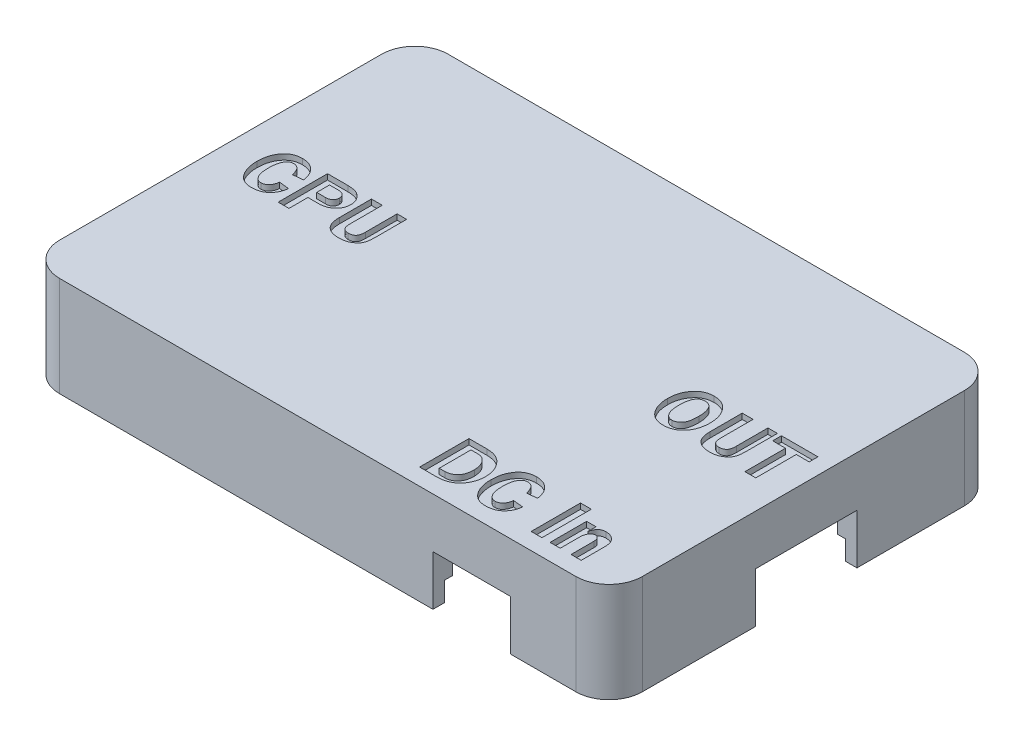
SolidWorks part; units mm, degrees
ref_plane "Front Plane" through (0, 0, 0) normal (0, 0, 1) x (1, 0, 0)
ref_plane "Top Plane" through (0, 0, 0) normal (0, 1, 0) x (1, 0, 0)
ref_plane "Right Plane" through (0, 0, 0) normal (1, 0, 0) x (0, 0, -1)
sketch "Sketch1" plane through (0, 0, 0) normal (0, 1, 0) x (1, 0, 0)
  line L1 (-52.5, 35) -> (52.5, 35)
  line L2 (-52.5, 35) -> (-52.5, -35)
  line L3 (-52.5, -35) -> (52.5, -35)
  line L4 (52.5, 35) -> (52.5, -35)
  line L5 (-52.5, 35) -> (52.5, -35) construction
  line L6 (-52.5, -35) -> (52.5, 35) construction
  point P0 (0, 0)
  dimension "D1" = 105
  dimension "D2" = 70
extrude "Boss-Extrude1" add sketch "Sketch1" along normal blind 15
sketch "Sketch3" plane through (0, 15, 0) normal (0, 1, 0) x (1, 0, 0)
  line L0 (52.5, -35) -> (52.5, 35) construction
  line L1 (49, -31.5) -> (-49, -31.5)
  line L2 (49, -31.5) -> (49, 31.5)
  line L3 (49, 31.5) -> (-49, 31.5)
  line L4 (-49, -31.5) -> (-49, 31.5)
  line L5 (49, -31.5) -> (-49, 31.5) construction
  line L6 (49, 31.5) -> (-49, -31.5) construction
  line L7 (-52.5, -35) -> (52.5, -35) construction
  point P0 (0, 0)
  dimension "D1" = 3.5
  dimension "D2" = 3.5
extrude "Cut-Extrude1" cut sketch "Sketch3" against normal blind 12
fillet "Fillet1" radius 6 8 edges at (-52.5, 7.5, -35) (-52.5, 7.5, 35) (52.5, 7.5, -35) (52.5, 7.5, 35) (49, 9, -31.5) (-49, 9, -31.5) (-49, 9, 31.5) (49, 9, 31.5)
sketch "Sketch4" plane through (0, 3, 0) normal (0, 1, 0) x (1, 0, 0)
  line L0 (-43, -31.5) -> (43, -31.5) construction
  line L1 (49, -25.5) -> (49, 25.5) construction
  circle A0 centre (40, -22.5) radius 3.5
  circle A1 centre (40, 19.2) radius 3.5
  circle A2 centre (-36.1, -22.5) radius 3.5
  circle A3 centre (-36.1, 19.2) radius 3.5
  dimension "D5" = 7
  dimension "D6" = 76.1
  dimension "D1" = 41.7
  dimension "D2" = 9
  dimension "D3" = 76.1
  dimension "D4" = 9
  dimension "D7" = 41.7
extrude "Boss-Extrude2" [suppressed] add sketch "Sketch4" along normal blind 5
sketch "Sketch5" [suppressed] plane through (0, 8, 0) normal (0, 1, 0) x (1, 0, 0)
  circle A0 centre (-36.1, 19.2) radius 1
  circle A1 centre (-36.1, -22.5) radius 1
  circle A2 centre (40, -22.5) radius 1
  circle A3 centre (40, 19.0603) radius 1
  dimension "D1" = 2
extrude "Cut-Extrude2" [suppressed] cut sketch "Sketch5" against normal blind 8
sketch "Sketch6" plane through (0, 15, 0) normal (0, 1, 0) x (1, 0, 0)
  line L0 (49, -25.5) -> (49, 25.5) construction
  line L1 (49, 9.66) -> (52.5, 9.66)
  line L2 (49, 9.66) -> (49, -8.64)
  line L3 (49, -8.64) -> (52.5, -8.64)
  line L4 (52.5, 9.66) -> (52.5, -8.64)
  line L5 (52.5, -29) -> (52.5, 29) construction
  line L6 (-46.5, -35) -> (46.5, -35) construction
  line L7 (34.76, -35) -> (20.76, -35)
  line L8 (34.76, -35) -> (34.76, -31.5)
  line L9 (34.76, -31.5) -> (20.76, -31.5)
  line L10 (20.76, -35) -> (20.76, -31.5)
  line L11 (-43, -31.5) -> (43, -31.5) construction
  line L12 (-52.5, 29) -> (-52.5, -29) construction
  line L13 (-52.5, 10) -> (-49, 10)
  line L14 (-52.5, 10) -> (-52.5, -10)
  line L15 (-52.5, -10) -> (-49, -10)
  line L16 (-49, 10) -> (-49, -10)
  line L17 (-49, 25.5) -> (-49, -25.5) construction
  dimension "D1" = 14
  dimension "D2" = 20
  dimension "D3" = 25
  dimension "D4" = 14.24
  dimension "D5" = 22.86
  dimension "D6" = 18.3
extrude "Cut-Extrude3" cut sketch "Sketch6" against normal blind 26
sketch "Sketch9" plane through (0, 3, 0) normal (0, 1, 0) x (1, 0, 0)
  line L1 (-43, 31.5) -> (43, 31.5)
  line L2 (-49, 25.5) -> (-49, -25.5)
  line L3 (-43, -31.5) -> (43, -31.5)
  line L4 (49, 25.5) -> (49, -25.5)
  line L5 (-49, 31.5) -> (49, -31.5) construction
  line L6 (-49, -31.5) -> (49, 31.5) construction
  line L7 (-43, -31.5) -> (20.76, -31.5) construction
  arc A0 (-43, 31.5) -> (-49, 25.5) centre (-43, 25.5) ccw
  arc A1 (43, 31.5) -> (49, 25.5) centre (43, 25.5) cw
  arc A2 (43, -31.5) -> (49, -25.5) centre (43, -25.5) ccw
  arc A3 (-49, -25.5) -> (-43, -31.5) centre (-43, -25.5) ccw
  point P0 (0, 0)
  dimension "D3" = 6
  dimension "D2" = 0
extrude "Cut-Extrude4" cut sketch "Sketch9" against normal blind 10
sketch "Sketch10" plane through (0, 15, 0) normal (0, 1, 0) x (1, 0, 0)
  line L0 (-52.5, -10) -> (-52.5, -29) construction
  line L1 (-46.5, 35) -> (46.5, 35)
  line L2 (-52.5, 29) -> (-52.5, -29)
  line L3 (-46.5, -35) -> (46.5, -35)
  line L4 (52.5, 29) -> (52.5, -29)
  line L5 (-52.5, 35) -> (52.5, -35) construction
  line L6 (-52.5, -35) -> (52.5, 35) construction
  line L7 (-46.5, -35) -> (20.76, -35) construction
  arc A0 (46.5, -35) -> (52.5, -29) centre (46.5, -29) ccw
  arc A1 (46.5, 35) -> (52.5, 29) centre (46.5, 29) cw
  arc A2 (-46.5, 35) -> (-52.5, 29) centre (-46.5, 29) ccw
  arc A3 (-52.5, -29) -> (-46.5, -35) centre (-46.5, -29) ccw
  point P0 (0, 0)
  dimension "D3" = 6
  dimension "D1" = 0
  dimension "D2" = 0
extrude "Boss-Extrude3" add sketch "Sketch10" along normal blind 3
sketch "Sketch11" plane through (0, 0, 0) normal (0, -1, 0) x (-1, 0, 0)
  line L0 (-46.5, 35) -> (46.5, 35) construction
  line L1 (-44.4, 32.9) -> (44.4, 32.9)
  line L2 (-50.4, 26.9) -> (-50.4, -26.9)
  line L3 (-44.4, -32.9) -> (44.4, -32.9)
  line L4 (50.4, 26.9) -> (50.4, -26.9)
  line L5 (-50.4, 32.9) -> (50.4, -32.9) construction
  line L6 (-50.4, -32.9) -> (50.4, 32.9) construction
  line L7 (-52.5, -29) -> (-52.5, -8.64) construction
  arc A0 (44.4, -32.9) -> (50.4, -26.9) centre (44.4, -26.9) ccw
  arc A1 (44.4, 32.9) -> (50.4, 26.9) centre (44.4, 26.9) cw
  arc A2 (-44.4, 32.9) -> (-50.4, 26.9) centre (-44.4, 26.9) ccw
  arc A3 (-50.4, -26.9) -> (-44.4, -32.9) centre (-44.4, -26.9) ccw
  point P0 (0, 0)
  dimension "D3" = 6
  dimension "D1" = 2.1
  dimension "D2" = 2.1
extrude "Cut-Extrude5" cut sketch "Sketch11" against normal blind 3.5
sketch "Sketch12" plane through (0, 15, 0) normal (0, -1, 0) x (-1, 0, 0)
  line L1 (-52.5, 9.66) -> (-49, 9.66)
  line L2 (-52.5, 9.66) -> (-52.5, -8.64)
  line L3 (-52.5, -8.64) -> (-49, -8.64)
  line L4 (-49, 9.66) -> (-49, -8.64)
  line L5 (-20.76, -35) -> (-34.76, -35)
  line L6 (-20.76, -35) -> (-20.76, -31.5)
  line L7 (-20.76, -31.5) -> (-34.76, -31.5)
  line L8 (-34.76, -35) -> (-34.76, -31.5)
  line L9 (49, -10) -> (52.5, -10)
  line L10 (49, -10) -> (49, 10)
  line L11 (49, 10) -> (52.5, 10)
  line L12 (52.5, -10) -> (52.5, 10)
extrude "Boss-Extrude4" add sketch "Sketch12" along normal blind 6
sketch "Sketch13" plane through (0, 18, 0) normal (0, 1, 0) x (1, 0, 0)
  line L0 (-52.5, 29) -> (-52.5, -29) construction
  line L1 (-52.5, -0.4066) -> (52.5, -0.4066) construction
  line L2 (52.5, -29) -> (52.5, 29) construction
  line L3 (-46.5, -35) -> (46.5, -35) construction
  text T0 "<b>CPU</b>" font "Franklin Gothic Medium" height in points 36
  text T1 "DC In" font "Franklin Gothic Medium" height in points 36
  text T2 "OUT" font "Franklin Gothic Medium" height in points 36
  point P9 (0, -35)
  dimension "D1" = 5
  dimension "D2" = 3
  dimension "D3" = 3
  dimension "D4" = 38
  dimension "D5" = 26
  dimension "D6" = 3
extrude "Cut-Extrude6" cut sketch "Sketch13" against normal blind 1
equation "\"D2@Sketch3\"=\"D1@Sketch3\""
equation "\"D4@Sketch4\"=\"D2@Sketch4\""
equation "\"D6@Sketch4\"=\"D3@Sketch4\""
equation "\"D7@Sketch4\"=\"D1@Sketch4\""
